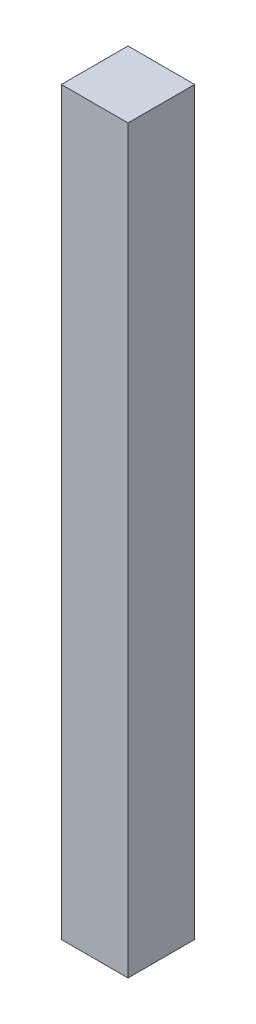
SolidWorks part; units mm, degrees
ref_plane "Front Plane" through (0, 0, 0) normal (0, 0, 1) x (1, 0, 0)
ref_plane "Top Plane" through (0, 0, 0) normal (0, 1, 0) x (1, 0, 0)
ref_plane "Right Plane" through (0, 0, 0) normal (1, 0, 0) x (0, 0, -1)
other "Configuration Table"
sketch "Sketch1" plane through (0, 0, 0) normal (0, 0, 1) x (1, 0, 0)
  line L1 (45, 490) -> (63, 490)
  line L2 (45, 490) -> (45, 690)
  line L3 (45, 690) -> (63, 690)
  line L4 (63, 490) -> (63, 690)
extrude "TOPPING_klape_alt1_gazli_amortisor_1_1" add sketch "Sketch1" along normal blind 18 from offset 8 separate body
